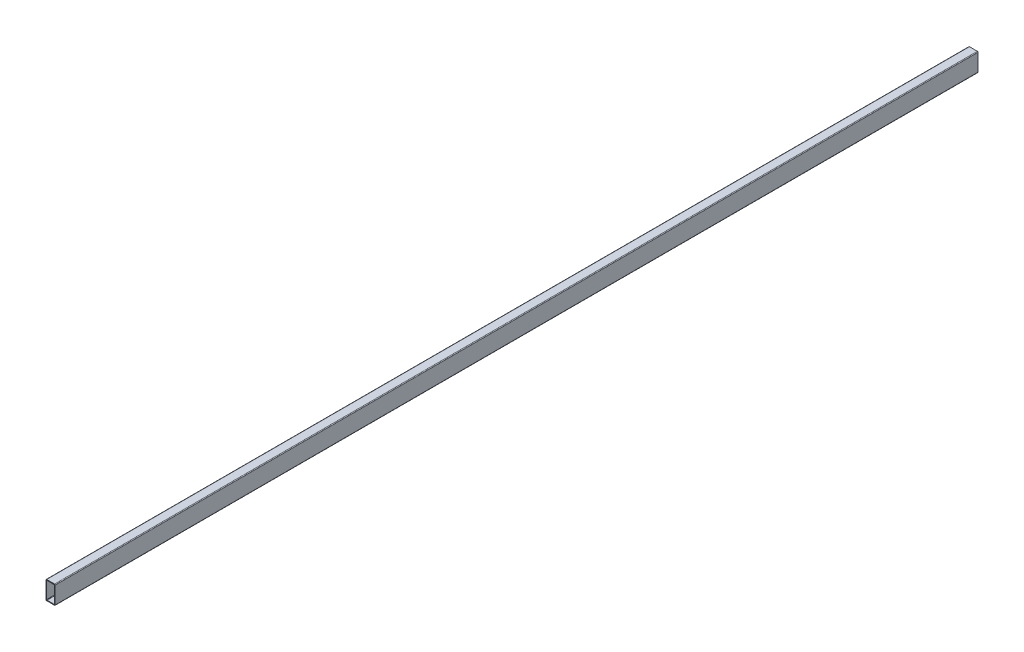
SolidWorks part; units mm, degrees
material "СТ3КП"
ref_plane "Спереди" through (0, 0, 0) normal (0, 0, 1) x (1, 0, 0)
ref_plane "Сверху" through (0, 0, 0) normal (0, 1, 0) x (1, 0, 0)
ref_plane "Справа" through (0, 0, 0) normal (1, 0, 0) x (0, 0, -1)
sketch "Эскиз1" plane through (0, 0, 0) normal (0, 0, 1) x (1, 0, 0)
  point P0 (25.6841, 42.0862)
  line B0 (0, 38.5) -> (0, 1.5)
  line B1 (1.5, 40) -> (18.5, 40)
  line B2 (20, 38.5) -> (20, 1.5)
  line B3 (1.5, 0) -> (18.5, 0)
  line B4 (1.5, 37.5) -> (1.5, 2.5)
  line B5 (2.5, 38.5) -> (17.5, 38.5)
  line B6 (18.5, 37.5) -> (18.5, 2.5)
  line B7 (2.5, 1.5) -> (17.5, 1.5)
  arc B8 (18.5, 40) -> (20, 38.5) centre (18.5, 38.5) cw
  arc B9 (20, 1.5) -> (18.5, 0) centre (18.5, 1.5) cw
  arc B10 (0, 1.5) -> (1.5, 0) centre (1.5, 1.5) ccw
  arc B11 (0, 38.5) -> (1.5, 40) centre (1.5, 38.5) cw
  arc B12 (18.5, 2.5) -> (17.5, 1.5) centre (17.5, 2.5) cw
  arc B13 (17.5, 38.5) -> (18.5, 37.5) centre (17.5, 37.5) cw
  arc B14 (1.5, 37.5) -> (2.5, 38.5) centre (2.5, 37.5) cw
  arc B15 (1.5, 2.5) -> (2.5, 1.5) centre (2.5, 2.5) ccw
sketch_block_instance "40х20х1_5-1"
sketch_block "40х20х1_5" parameters "D5"=1.5, "D6"=1, "D1"=1.5, "D2"=1.5, "D3"=40, "D4"=20, "D7"=14, "D8"=33
extrude "Бобышка-Вытянуть1" add sketch "Эскиз1" along normal up to vertex (1000 mm away)
mirror "Зеркальное отражение1" about plane through (18.5, 38.5, 0) normal (0, 0, -1) of "Бобышка-Вытянуть1"
equation "\"D2@40х20х1_5\"=\"D1@40х20х1_5\""
equation "\"D7@40х20х1_5\"=\"D1@40х20х1_5\""
equation "\"D8@40х20х1_5\"=\"D1@40х20х1_5\""
equation "\"D5@40х20х1_5\"=\"D1@40х20х1_5\""
equation "\"D6@40х20х1_5\"=\"D5@40х20х1_5\"-0.5"
